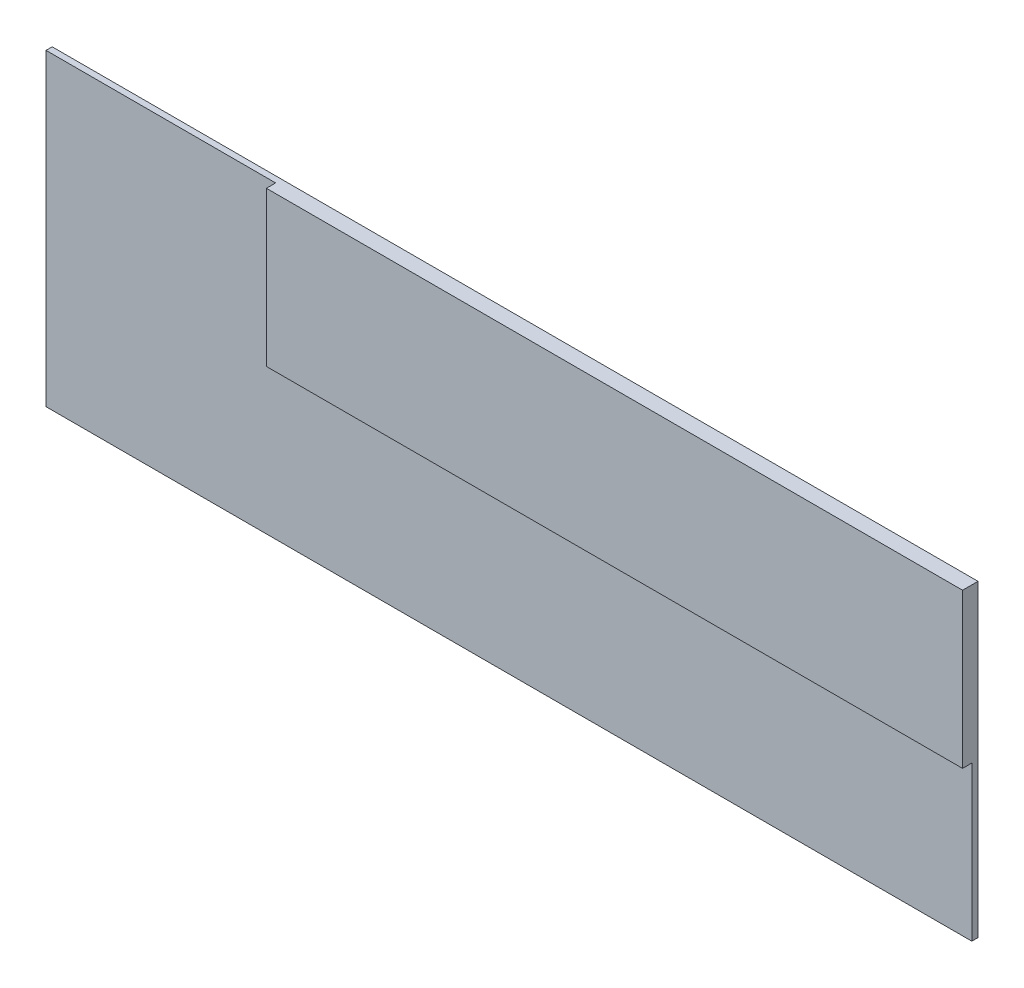
SolidWorks part; units mm, degrees
ref_plane "Front Plane" through (0, 0, 0) normal (0, 0, 1) x (1, 0, 0)
ref_plane "Top Plane" through (0, 0, 0) normal (0, 1, 0) x (1, 0, 0)
ref_plane "Right Plane" through (0, 0, 0) normal (1, 0, 0) x (0, 0, -1)
sketch "Sketch1" plane through (0, 0, 0) normal (0, 0, 1) x (1, 0, 0)
  line L1 (-2500, 2500) -> (12500, 2500)
  line L2 (-2500, 2500) -> (-2500, -2500)
  line L3 (-2500, -2500) -> (12500, -2500)
  line L4 (12500, 2500) -> (12500, -2500)
  line L5 (-2500, 2500) -> (12500, -2500) construction
  line L6 (-2500, -2500) -> (12500, 2500) construction
  point P0 (5000, 0)
  dimension "D1" = 15000
  dimension "D2" = 5000
  dimension "D3" = 5000
extrude "Boss-Extrude1" add sketch "Sketch1" against normal blind 100
sketch "Sketch2" plane through (0, 0, 0) normal (0, 0, 1) x (1, 0, 0)
  line L0 (12500, -2500) -> (12500, 2500) construction
  line L1 (1220.82, 0) -> (12500, 0)
  line L2 (1220.82, 0) -> (1220.82, 2500)
  line L3 (1220.82, 2500) -> (12500, 2500)
  line L4 (12500, 0) -> (12500, 2500)
  line L5 (12500, 2500) -> (-2500, 2500) construction
extrude "Boss-Extrude2" add sketch "Sketch2" along normal blind 150
